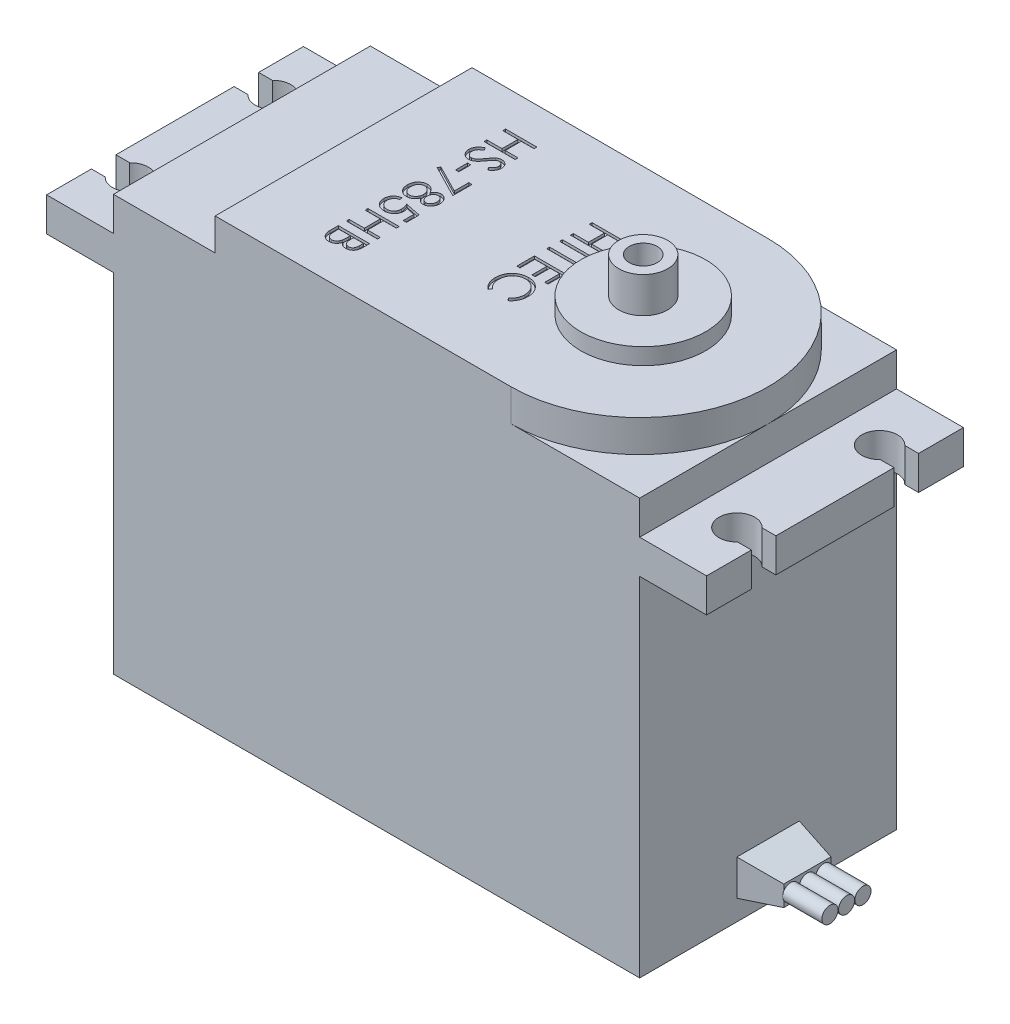
SolidWorks part; units mm, degrees
material "ABS"
ref_plane "Front Plane" through (0, 0, 0) normal (0, 0, 1) x (1, 0, 0)
ref_plane "Top Plane" through (0, 0, 0) normal (0, 1, 0) x (1, 0, 0)
ref_plane "Right Plane" through (0, 0, 0) normal (1, 0, 0) x (0, 0, -1)
sketch "Sketch1" plane through (0, 0, 0) normal (0, 0, 1) x (1, 0, 0)
  line L1 (0, 0) -> (59, 0)
  line L2 (0, 0) -> (0, 46.6)
  line L3 (0, 46.6) -> (59, 46.6)
  line L4 (59, 0) -> (59, 46.6)
  dimension "D1" = 59
  dimension "D2" = 46.6
extrude "Boss-Extrude1" add sketch "Sketch1" along normal blind 28.8
sketch "Sketch2" plane through (0, 46.6, 0) normal (0, 1, 0) x (1, 0, 0)
  line L0 (59, 0) -> (0, 0) construction
  line L1 (11.4, 0) -> (44.6, 0)
  line L2 (11.4, 0) -> (11.4, -28.8)
  line L3 (11.4, -28.8) -> (44.6, -28.8)
  line L4 (44.6, 0) -> (44.6, -28.8) construction
  line L5 (59, -28.8) -> (0, -28.8) construction
  line L6 (59, -28.8) -> (59, 0) construction
  arc A0 (44.6, -28.8) -> (44.6, 0) centre (44.6, -14.4) ccw
  dimension "D1" = 47.6
extrude "Boss-Extrude2" add sketch "Sketch2" along normal blind 3.6
sketch "Sketch3" plane through (0, 50.2, 0) normal (0, 1, 0) x (1, 0, 0)
  line L0 (0, -14.4) -> (59, -14.4) construction
  line L1 (0, -28.8) -> (0, 0) construction
  line L2 (59, -14.4) -> (59, 0) construction
  circle A0 centre (45, -14.4) radius 7
  dimension "D1" = 14
  dimension "D2" = 14
extrude "Boss-Extrude3" add sketch "Sketch3" along normal blind 1.85
ref_plane "Plane1" through (0, 39, 0) normal (0, -1, 0) x (-1, 0, 0)
sketch "Sketch4" plane through (0, 39, 0) normal (0, -1, 0) x (-1, 0, 0)
  line L0 (-29.5, -28.8) -> (-29.5, 0) construction
  line L1 (-66.5, 0) -> (7.5, 0)
  line L2 (-66.5, 0) -> (-66.5, -5.025)
  line L3 (-66.5, -28.8) -> (7.5, -28.8)
  line L4 (7.5, 0) -> (7.5, -5.025)
  line L5 (0, -28.8) -> (-59, -28.8) construction
  line L6 (-29.5, -14.4) -> (7.5, -14.4) construction
  line L7 (-66.5, -7.775) -> (-66.5, -21.025)
  line L8 (-64.9524, -5.025) -> (-66.5, -5.025)
  line L9 (-63.5, -6.4) -> (-70.0561, -6.4) construction
  line L10 (-64.9524, -7.775) -> (-66.5, -7.775)
  line L11 (0, 0) -> (-59, 0) construction
  line L12 (5.9524, -7.775) -> (7.5, -7.775)
  line L13 (5.9524, -5.025) -> (7.5, -5.025)
  line L14 (5.9524, -23.775) -> (7.5, -23.775)
  line L15 (5.9524, -21.025) -> (7.5, -21.025)
  line L16 (-64.9524, -21.025) -> (-66.5, -21.025)
  line L17 (-64.9524, -23.775) -> (-66.5, -23.775)
  line L18 (7.5, -23.775) -> (7.5, -28.8)
  line L19 (7.5, -7.775) -> (7.5, -21.025)
  line L20 (-66.5, -23.775) -> (-66.5, -28.8)
  arc A0 (-64.9524, -7.775) -> (-64.9524, -5.025) centre (-63.5, -6.4) ccw
  arc A1 (5.9524, -7.775) -> (5.9524, -5.025) centre (4.5, -6.4) cw
  arc A2 (5.9524, -21.025) -> (5.9524, -23.775) centre (4.5, -22.4) ccw
  arc A3 (-64.9524, -21.025) -> (-64.9524, -23.775) centre (-63.5, -22.4) cw
  dimension "D4" = 4
  dimension "D1" = 74
  dimension "D2" = 68
  dimension "D3" = 16
  dimension "D5" = 2.75
extrude "Boss-Extrude4" add sketch "Sketch4" against normal blind 3.8
sketch "Sketch5" plane through (59, 0, 0) normal (1, 0, 0) x (0, 0, -1)
  line L0 (-14.4, 0) -> (-14.4, 22.5509) construction
  line L1 (-28.8, 0) -> (0, 0) construction
  line L3 (-17.9, 6.3) -> (-10.9, 6.3)
  line L4 (-17.9, 6.3) -> (-17.9, 2.3)
  line L5 (-17.9, 2.3) -> (-10.9, 2.3)
  line L6 (-10.9, 6.3) -> (-10.9, 2.3)
  line L7 (-17.9, 6.3) -> (-10.9, 2.3) construction
  line L8 (-17.9, 2.3) -> (-10.9, 6.3) construction
  point P4 (-14.4, 4.3)
  dimension "D1" = 7
  dimension "D2" = 4
  dimension "D3" = 2.3
extrude "Boss-Extrude5" add sketch "Sketch5" along normal blind 4.4 draft 11
sketch "Sketch6" plane through (63.4, 0, 0) normal (1, 0, 0) x (0, 0, -1)
  line L0 (-17.0447, 4.3) -> (-11.7553, 4.3) construction
  line L1 (-17.0447, 5.4447) -> (-17.0447, 3.1553) construction
  line L2 (-11.7553, 3.1553) -> (-11.7553, 5.4447) construction
  circle A0 centre (-14.4, 4.3) radius 0.903
  circle A1 centre (-12.5627, 4.3) radius 0.903
  circle A2 centre (-16.2659, 4.3) radius 0.903
extrude "Boss-Extrude6" add sketch "Sketch6" along normal blind 4.4
sketch "Sketch7" plane through (0, 52.05, 0) normal (0, 1, 0) x (1, 0, 0)
  circle A0 centre (45, -14.4) radius 2.75
  dimension "D1" = 5.5
extrude "Boss-Extrude7" add sketch "Sketch7" along normal blind 4
hole_wizard "Tap Drill for M3 Helicoil1" positions "Sketch9" profile "Sketch8" hole size "M3x0.5" standard "ANSI Metric"
sketch "Sketch9" plane through (0, 56.05, 0) normal (0, 1, 0) x (1, 0, 0)
  point P0 (45, -14.4)
sketch "Sketch8" plane through (45, 56.05, 14.4) normal (1, 0, 0) x (0, 0, 1)
  line L0 (0, 0) -> (0, 3.9464)
  line L1 (0, 3.9464) -> (1.575, 3)
  line L2 (1.575, 3) -> (1.575, 0)
  line L5 (1.575, 0) -> (0, 0)
  line L10 (0, 3.9464) -> (-1.575, 3) construction
  line L11 (0, -6.35) -> (0, 107.95) construction
  dimension "Hole Dia." = 3.15
  dimension "Hole Depth" = 3
  dimension "Drill Angle" = 118
sketch "Sketch10" plane through (0, 50.2, 0) normal (0, 1, 0) x (1, 0, 0)
  line L0 (33.1833, 0) -> (33.1833, -28.8) construction
  line L1 (11.4, -28.8) -> (44.6, -28.8) construction
  text T0 "HITEC\r\n\r\nHS-785HB"
extrude "Cut-Extrude1" cut sketch "Sketch10" against normal blind 0.3
